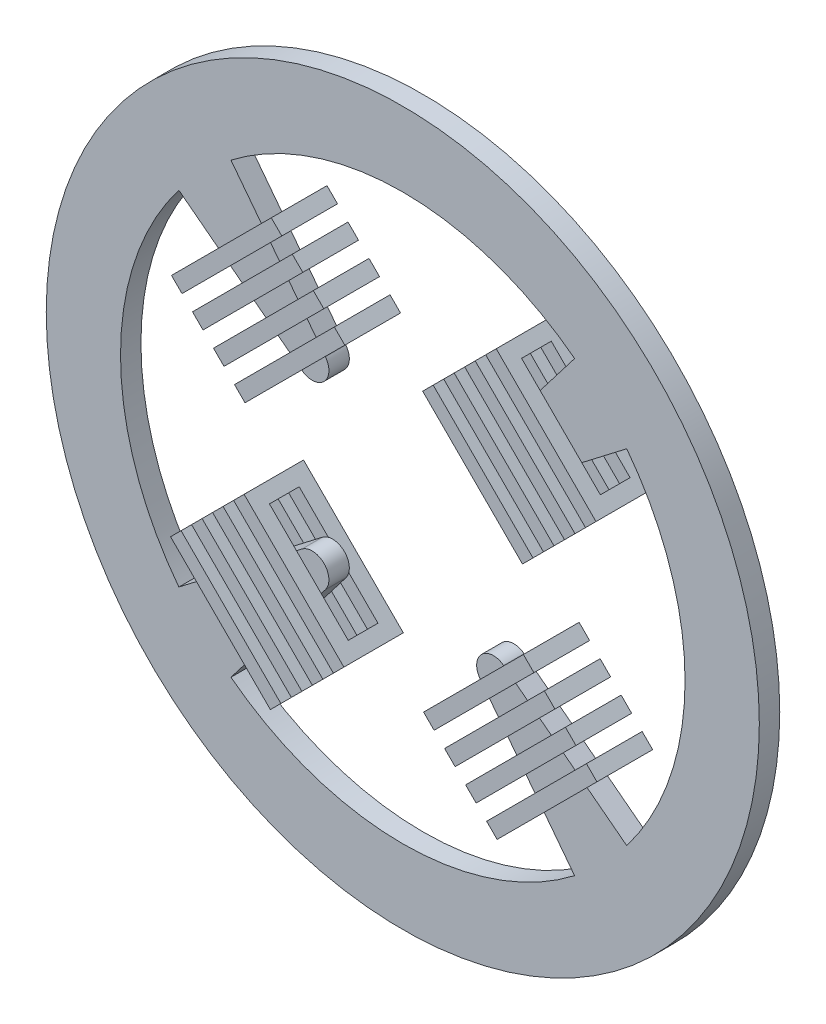
SolidWorks part; units mm, degrees
other "標示1"
sketch "草圖65"
ref_plane "前基準面" through (0, 0, 0) normal (0, 0, 1) x (1, 0, 0)
ref_plane "上基準面" through (0, 0, 0) normal (0, 1, 0) x (1, 0, 0)
ref_plane "右基準面" through (0, 0, 0) normal (1, 0, 0) x (0, 0, -1)
sketch "草圖1" plane through (0, 0, 0) normal (0, 0, 1) x (1, 0, 0)
  circle A0 centre (0, 0) radius 0.96
  circle A1 centre (0, 0) radius 0.76
extrude "填料-伸長1" add sketch "草圖1" along normal blind 0.055
sketch "草圖2" plane through (0, 0, 0.055) normal (0, 0, 1) x (1, 0, 0)
  line L0 (0, 0) -> (0, 1.565) construction
  line L1 (0, 0) -> (-1.8584, 0) construction
  line L2 (-0.0447, 0.3392) -> (-0.0992, 0.7535)
  line L3 (0.0447, 0.3392) -> (0.0992, 0.7535)
  line L4 (0.2714, 0.2082) -> (0.6029, 0.4627)
  line L5 (0.2082, 0.2714) -> (0.4627, 0.6029)
  line L6 (0.2082, -0.2714) -> (0.4627, -0.6029)
  line L7 (0.2714, -0.2082) -> (0.6029, -0.4627)
  line L8 (-0.2714, -0.2082) -> (-0.6029, -0.4627)
  line L9 (-0.2082, -0.2714) -> (-0.4627, -0.6029)
  line L10 (-0.2082, 0.2714) -> (-0.4627, 0.6029)
  line L11 (-0.2714, 0.2082) -> (-0.6029, 0.4627)
  circle A0 centre (0, 0) radius 0.3
  circle A1 centre (0, 0) radius 0.76 construction
  arc A3 (-0.0447, 0.3392) -> (0.0447, 0.3392) centre (0, 0.345) ccw
  arc A4 (0.0992, 0.7535) -> (-0.0992, 0.7535) centre (0, 0) ccw
  arc A5 (-0.76, 0) -> (0.76, 0) centre (0, 0) ccw
  arc A6 (0.6029, 0.4627) -> (0.4627, 0.6029) centre (0, 0) ccw
  arc A7 (0.2082, 0.2714) -> (0.2714, 0.2082) centre (0.244, 0.244) ccw
  arc A8 (0.4627, -0.6029) -> (0.6029, -0.4627) centre (0, 0) ccw
  arc A9 (0.2714, -0.2082) -> (0.2082, -0.2714) centre (0.244, -0.244) ccw
  arc A10 (-0.6029, -0.4627) -> (-0.4627, -0.6029) centre (0, 0) ccw
  arc A11 (-0.2082, -0.2714) -> (-0.2714, -0.2082) centre (-0.244, -0.244) ccw
  arc A12 (-0.4627, 0.6029) -> (-0.6029, 0.4627) centre (0, 0) ccw
  arc A13 (-0.2714, 0.2082) -> (-0.2082, 0.2714) centre (-0.244, 0.244) ccw
  point P23 (0, 0)
  point P34 (0, 0)
  point P41 (0, 0)
  circle M4 centre (0, 0) radius 0.76
  dimension "D1" = 7.5
  dimension "D3" = 2
  dimension "D4" = 4
  dimension "D2" = 7.5
extrude "填料-伸長2" add sketch "草圖2" against normal blind 0.055 contours L11 A13 L10 M4 | L5 A7 L4 M4 | L7 A9 L6 M4 | A11 L8 L9 M4
sketch "草圖7" plane through (0, 0, 0.055) normal (0, 0, 1) x (1, 0, 0)
  line L0 (0.2121, 0.2121) -> (0.2404, 0.2404) construction
  line L1 (0.2404, 0.2404) -> (0.2013, 0.2795) construction
  line L2 (0.2404, 0.2404) -> (0.5894, 0.5894) construction
  line L3 (0.0244, -0.0244) -> (-0.6648, 0.6648) construction
  line L4 (0.2404, -0.2404) -> (0.3328, -0.148)
  arc A0 (0.2082, 0.2714) -> (0.2714, 0.2082) centre (0.244, 0.244) ccw construction
  arc A1 (-0.2082, -0.2714) -> (-0.2714, -0.2082) centre (-0.244, -0.244) ccw construction
  arc A2 (-0.2714, 0.2082) -> (-0.2082, 0.2714) centre (-0.244, 0.244) ccw construction
  arc A3 (0.2714, -0.2082) -> (0.2082, -0.2714) centre (0.244, -0.244) ccw construction
  point P5 (0.297, 0.297)
  point P7 (-0.2121, -0.2121)
  point P8 (0.3536, 0.3536)
  point P9 (0.4101, 0.4101)
  point P12 (-0.2404, -0.2404)
  point P16 (-0.297, -0.297)
  point P17 (-0.3536, -0.3536)
  point P18 (-0.4101, -0.4101)
  point P20 (0.2404, -0.2404)
  point P23 (-0.2404, 0.2404)
  point P24 (-0.2121, 0.2121)
  point P25 (0.2121, -0.2121)
  point P29 (0.297, -0.297)
  point P33 (0.3536, -0.3536)
  point P34 (0.4101, -0.4101)
  point P35 (-0.297, 0.297)
  point P36 (-0.3536, 0.3536)
  point P37 (-0.4101, 0.4101)
  point P40 (0.4667, -0.4667)
  point P41 (0.5233, -0.5233)
  point P42 (0.4667, 0.4667)
  point P43 (0.5233, 0.5233)
  point P44 (-0.4667, 0.4667)
  point P45 (-0.5233, 0.5233)
  point P46 (-0.4667, -0.4667)
  point P47 (-0.5233, -0.5233)
  point P48 (0, 0)
  dimension "D1" = 0.08
  dimension "D2" = 0.08
  dimension "D3" = 0.08
  dimension "D4" = 0.04
  dimension "D5" = 0.04
  dimension "D6" = 0.08
  dimension "D7" = 0.08
  dimension "D8" = 0.08
  dimension "D9" = 0.04
  dimension "D10" = 0.04
  dimension "D11" = 0.08
  dimension "D12" = 0.08
  dimension "D13" = 0.08
  dimension "D14" = 0.08
  dimension "D15" = 0.08
  dimension "D16" = 0.08
  dimension "D17" = 0.08
  dimension "D18" = 0.08
  dimension "D19" = 0.08
  dimension "D20" = 0.08
  dimension "D21" = 0.08
  dimension "D22" = 0.08
  dimension "D23" = 0.08
  dimension "D24" = 0.08
ref_plane "平面5" through (0.2404, 0.2404, 0) normal (0.7071, 0.7071, 0) x (-0.7071, 0.7071, 0)
sketch "草圖11" plane through (0.2404, 0.2404, 0) normal (0.7071, 0.7071, 0) x (-0.7071, 0.7071, 0)
  line L0 (0, 0.055) -> (0, 0.1261) construction
  line L1 (-0.15, 0.0675) -> (0.15, 0.0675)
  line L2 (0.19, 0.1075) -> (-0.19, 0.1075)
  line L7 (-0.19, -0.0525) -> (0.19, -0.0525)
  line L17 (0.19, 0.1075) -> (0.19, -0.0525)
  line L18 (-0.19, 0.1075) -> (-0.19, -0.0525)
  line L19 (-0.15, -0.0125) -> (0.15, -0.0125)
  line L20 (-0.15, 0.0675) -> (-0.15, -0.0125)
  line L21 (0.15, 0.0675) -> (0.15, -0.0125)
  point P1 (0, 0.0275)
  point P2 (0, -0.0125)
  point P9 (0, 0.055)
  point P10 (0, -0.0525)
  point P11 (0, 0)
  point P13 (0, 0.1075)
  point P16 (0, -0.0525)
  point P19 (0, 0.0675)
  point P21 (0, 0.0675)
  point P22 (0, 0.1075)
  point P24 (0, -0.0125)
  dimension "D1" = 0.04
  dimension "D2" = 0.04
  dimension "D3" = 0.38
  dimension "D4" = 0.04
  dimension "D7" = 0.04
extrude "填料-伸長3" add sketch "草圖11" along normal blind 0.04 separate body
ref_plane "平面6" through (0.297, 0.297, 0) normal (0.7071, 0.7071, 0) x (0.7071, -0.7071, 0)
ref_plane "平面7" through (0.3536, 0.3536, 0) normal (0.7071, 0.7071, 0) x (0.7071, -0.7071, 0)
ref_plane "平面8" through (0.4101, 0.4101, 0) normal (0.7071, 0.7071, 0) x (0.7071, -0.7071, 0)
ref_plane "平面9" through (-0.2404, -0.2404, 0) normal (0.7071, 0.7071, 0) x (0.7071, -0.7071, 0)
ref_plane "平面10" through (-0.297, -0.297, 0) normal (0.7071, 0.7071, 0) x (0.7071, -0.7071, 0)
ref_plane "平面11" through (-0.3536, -0.3536, 0) normal (0.7071, 0.7071, 0) x (0.7071, -0.7071, 0)
ref_plane "平面12" through (-0.4101, -0.4101, 0) normal (0.7071, 0.7071, 0) x (0.7071, -0.7071, 0)
ref_plane "平面13" through (0.2404, -0.2404, 0) normal (0.7071, -0.7071, 0) x (0.7071, 0.7071, 0)
ref_plane "平面14" through (0.297, -0.297, 0) normal (0.7071, -0.7071, 0) x (0, 0, -1)
ref_plane "平面15" through (0.3536, -0.3536, 0) normal (0.7071, -0.7071, 0) x (0, 0, -1)
ref_plane "平面16" through (0.4101, -0.4101, 0) normal (0.7071, -0.7071, 0) x (0, 0, -1)
ref_plane "平面17" through (-0.2404, 0.2404, 0) normal (0.7071, -0.7071, 0) x (0, 0, -1)
ref_plane "平面18" through (-0.297, 0.297, 0) normal (0.7071, -0.7071, 0) x (0, 0, -1)
ref_plane "平面19" through (-0.3536, 0.3536, 0) normal (0.7071, -0.7071, 0) x (0, 0, -1)
ref_plane "平面20" through (-0.4101, 0.4101, 0) normal (0.7071, -0.7071, 0) x (0, 0, -1)
sketch "草圖60" plane through (0.2404, -0.2404, 0) normal (0.7071, -0.7071, 0) x (0.7071, 0.7071, 0)
sketch "草圖62" plane through (0.2404, -0.2404, 0) normal (0.7071, -0.7071, 0) x (0.7071, 0.7071, 0)
  line L0 (0, -0.0586) -> (0, 0.1686)
  line L2 (0.15, 0.065) -> (-0.15, 0.065)
  line L3 (-0.15, 0.065) -> (-0.15, -0.005)
  line L4 (-0.15, -0.005) -> (0.15, -0.005)
  line L5 (0.15, -0.005) -> (0.15, 0.065)
  line L6 (0.19, 0.105) -> (-0.19, 0.105)
  line L7 (-0.19, 0.105) -> (-0.19, -0.045)
  line L8 (-0.19, -0.045) -> (0.19, -0.045)
  line L9 (0.19, -0.045) -> (0.19, 0.105)
  point P0 (0, 0.065)
  point P4 (0, 0.055)
  point P5 (0, -0.005)
  point P8 (0, 0.105)
  point P11 (0, 0.065)
  point P14 (0, -0.045)
  point P18 (0, 0.105)
  dimension "D1" = 0.01
  dimension "D2" = 0.06
  dimension "D3" = 0.04
  dimension "D4" = 0.04
  dimension "D5" = 0.38
  dimension "D6" = 0.3
sketch "草圖64" plane through (0.297, -0.297, 0) normal (0.7071, -0.7071, 0) x (0, 0, -1)
  line L0 (0.045, 0.19) -> (-0.105, 0.19) construction
  line L1 (0.005, 0.15) -> (-0.065, 0.15) construction
  line L2 (0.045, -0.19) -> (0.045, 0.19) construction
  line L3 (0.005, -0.15) -> (0.005, 0.15) construction
  line L4 (-0.065, -0.15) -> (0.005, -0.15) construction
  line L5 (-0.065, 0.15) -> (-0.065, -0.15) construction
  line L6 (-0.105, -0.19) -> (0.045, -0.19) construction
  line L7 (-0.105, 0.19) -> (-0.105, -0.19) construction
  line L8 (0.045, 0.19) -> (-0.105, 0.19)
  line L9 (0.005, 0.15) -> (-0.065, 0.15)
  line L10 (0.045, -0.19) -> (0.045, 0.19)
  line L11 (0.005, -0.15) -> (0.005, 0.15)
  line L12 (-0.065, -0.15) -> (0.005, -0.15)
  line L13 (-0.065, 0.15) -> (-0.065, -0.15)
  line L14 (-0.105, -0.19) -> (0.045, -0.19)
  line L15 (-0.105, 0.19) -> (-0.105, -0.19)
sketch "草圖68" plane through (0.3536, -0.3536, 0) normal (0.7071, -0.7071, 0) x (0, 0, -1)
  line L0 (-0.105, -0.19) -> (0.045, -0.19) construction
  line L1 (-0.065, -0.15) -> (0.005, -0.15) construction
  line L2 (0.005, -0.15) -> (0.005, 0.15) construction
  line L3 (-0.065, 0.15) -> (-0.065, -0.15) construction
  line L4 (0.005, 0.15) -> (-0.065, 0.15) construction
  line L5 (0.045, -0.19) -> (0.045, 0.19) construction
  line L6 (0.045, 0.19) -> (-0.105, 0.19) construction
  line L7 (-0.105, 0.19) -> (-0.105, -0.19) construction
  line L8 (-0.105, -0.19) -> (0.045, -0.19)
  line L9 (-0.065, -0.15) -> (0.005, -0.15)
  line L10 (0.005, -0.15) -> (0.005, 0.15)
  line L11 (-0.065, 0.15) -> (-0.065, -0.15)
  line L12 (0.005, 0.15) -> (-0.065, 0.15)
  line L13 (0.045, -0.19) -> (0.045, 0.19)
  line L14 (0.045, 0.19) -> (-0.105, 0.19)
  line L15 (-0.105, 0.19) -> (-0.105, -0.19)
sketch "草圖69" plane through (0.4101, -0.4101, 0) normal (0.7071, -0.7071, 0) x (0, 0, -1)
  line L0 (0.045, -0.19) -> (0.045, 0.19) construction
  line L1 (0.045, 0.19) -> (-0.105, 0.19) construction
  line L2 (-0.105, 0.19) -> (-0.105, -0.19) construction
  line L3 (-0.105, -0.19) -> (0.045, -0.19) construction
  line L4 (-0.065, -0.15) -> (0.005, -0.15) construction
  line L5 (0.005, -0.15) -> (0.005, 0.15) construction
  line L6 (-0.065, 0.15) -> (-0.065, -0.15) construction
  line L7 (0.005, 0.15) -> (-0.065, 0.15) construction
  line L8 (0.045, -0.19) -> (0.045, 0.19)
  line L9 (0.045, 0.19) -> (-0.105, 0.19)
  line L10 (-0.105, 0.19) -> (-0.105, -0.19)
  line L11 (-0.105, -0.19) -> (0.045, -0.19)
  line L12 (-0.065, -0.15) -> (0.005, -0.15)
  line L13 (0.005, -0.15) -> (0.005, 0.15)
  line L14 (-0.065, 0.15) -> (-0.065, -0.15)
  line L15 (0.005, 0.15) -> (-0.065, 0.15)
sketch "草圖70" plane through (-0.2404, 0.2404, 0) normal (0.7071, -0.7071, 0) x (0, 0, -1)
  line L0 (-0.105, 0.19) -> (-0.105, -0.19) construction
  line L1 (-0.105, -0.19) -> (0.045, -0.19) construction
  line L2 (-0.065, -0.15) -> (0.005, -0.15) construction
  line L3 (-0.065, 0.15) -> (-0.065, -0.15) construction
  line L4 (0.005, -0.15) -> (0.005, 0.15) construction
  line L5 (0.005, 0.15) -> (-0.065, 0.15) construction
  line L6 (0.045, -0.19) -> (0.045, 0.19) construction
  line L7 (0.045, 0.19) -> (-0.105, 0.19) construction
  line L8 (-0.105, 0.19) -> (-0.105, -0.19)
  line L9 (-0.105, -0.19) -> (0.045, -0.19)
  line L10 (-0.065, -0.15) -> (0.005, -0.15)
  line L11 (-0.065, 0.15) -> (-0.065, -0.15)
  line L12 (0.005, -0.15) -> (0.005, 0.15)
  line L13 (0.005, 0.15) -> (-0.065, 0.15)
  line L14 (0.045, -0.19) -> (0.045, 0.19)
  line L15 (0.045, 0.19) -> (-0.105, 0.19)
sketch "草圖71" plane through (-0.297, 0.297, 0) normal (0.7071, -0.7071, 0) x (0, 0, -1)
  line L0 (0.045, -0.19) -> (0.045, 0.19) construction
  line L1 (-0.105, -0.19) -> (0.045, -0.19) construction
  line L2 (-0.065, -0.15) -> (0.005, -0.15) construction
  line L3 (0.005, -0.15) -> (0.005, 0.15) construction
  line L4 (-0.065, 0.15) -> (-0.065, -0.15) construction
  line L5 (0.005, 0.15) -> (-0.065, 0.15) construction
  line L6 (-0.105, 0.19) -> (-0.105, -0.19) construction
  line L7 (0.045, 0.19) -> (-0.105, 0.19) construction
  line L8 (0.045, -0.19) -> (0.045, 0.19)
  line L9 (-0.105, -0.19) -> (0.045, -0.19)
  line L10 (-0.065, -0.15) -> (0.005, -0.15)
  line L11 (0.005, -0.15) -> (0.005, 0.15)
  line L12 (-0.065, 0.15) -> (-0.065, -0.15)
  line L13 (0.005, 0.15) -> (-0.065, 0.15)
  line L14 (-0.105, 0.19) -> (-0.105, -0.19)
  line L15 (0.045, 0.19) -> (-0.105, 0.19)
sketch "草圖72" plane through (-0.3536, 0.3536, 0) normal (0.7071, -0.7071, 0) x (0, 0, -1)
  line L0 (-0.105, -0.19) -> (0.045, -0.19) construction
  line L1 (-0.105, 0.19) -> (-0.105, -0.19) construction
  line L2 (-0.065, 0.15) -> (-0.065, -0.15) construction
  line L3 (0.005, -0.15) -> (0.005, 0.15) construction
  line L4 (0.005, 0.15) -> (-0.065, 0.15) construction
  line L5 (0.045, 0.19) -> (-0.105, 0.19) construction
  line L6 (0.045, -0.19) -> (0.045, 0.19) construction
  line L7 (-0.105, -0.19) -> (0.045, -0.19)
  line L8 (-0.105, 0.19) -> (-0.105, -0.19)
  line L9 (-0.065, 0.15) -> (-0.065, -0.15)
  line L10 (0.005, -0.15) -> (0.005, 0.15)
  line L11 (0.005, 0.15) -> (-0.065, 0.15)
  line L12 (0.045, 0.19) -> (-0.105, 0.19)
  line L13 (0.045, -0.19) -> (0.045, 0.19)
  line L14 (-0.065, -0.15) -> (0.005, -0.15)
sketch "草圖73" plane through (-0.4101, 0.4101, 0) normal (0.7071, -0.7071, 0) x (0, 0, -1)
  line L0 (-0.065, -0.15) -> (0.005, -0.15) construction
  line L1 (-0.105, -0.19) -> (0.045, -0.19) construction
  line L2 (-0.105, 0.19) -> (-0.105, -0.19) construction
  line L3 (-0.065, 0.15) -> (-0.065, -0.15) construction
  line L4 (0.005, 0.15) -> (-0.065, 0.15) construction
  line L5 (0.005, -0.15) -> (0.005, 0.15) construction
  line L6 (0.045, -0.19) -> (0.045, 0.19) construction
  line L7 (0.045, 0.19) -> (-0.105, 0.19) construction
  line L8 (-0.065, -0.15) -> (0.005, -0.15)
  line L9 (-0.105, -0.19) -> (0.045, -0.19)
  line L10 (-0.105, 0.19) -> (-0.105, -0.19)
  line L11 (-0.065, 0.15) -> (-0.065, -0.15)
  line L12 (0.005, 0.15) -> (-0.065, 0.15)
  line L13 (0.005, -0.15) -> (0.005, 0.15)
  line L14 (0.045, -0.19) -> (0.045, 0.19)
  line L15 (0.045, 0.19) -> (-0.105, 0.19)
sketch "草圖74" plane through (-0.3536, 0.3536, 0) normal (0.7071, -0.7071, 0) x (0, 0, -1)
  line L0 (-0.065, -0.15) -> (0.005, -0.15) construction
  line L1 (-0.065, -0.15) -> (0.005, -0.15)
extrude "填料-伸長28" add sketch "草圖62" along normal blind 0.04 separate body contours L8 L9 L6 L0 L2 L5 L4 | L7 L8 L0 L4 L3 L2 L6
extrude "填料-伸長29" add sketch "草圖64" along normal blind 0.04 separate body
extrude "填料-伸長30" add sketch "草圖68" along normal blind 0.04 separate body
extrude "填料-伸長31" add sketch "草圖69" along normal blind 0.04 separate body
extrude "填料-伸長32" add sketch "草圖70" against normal blind 0.04 separate body
extrude "填料-伸長33" add sketch "草圖71" against normal blind 0.04 separate body
extrude "填料-伸長34" add sketch "草圖72" against normal blind 0.04 separate body
extrude "填料-伸長35" add sketch "草圖73" against normal blind 0.04 separate body
sketch "草圖76" plane through (0.297, 0.297, 0) normal (0.7071, 0.7071, 0) x (0.7071, -0.7071, 0)
  line L0 (0.19, -0.1075) -> (0.19, 0.0525) construction
  line L1 (0.15, -0.0675) -> (0.15, 0.0125) construction
  line L2 (-0.19, -0.1075) -> (0.19, -0.1075) construction
  line L3 (0.15, -0.0675) -> (-0.15, -0.0675) construction
  line L4 (-0.15, -0.0675) -> (-0.15, 0.0125) construction
  line L5 (-0.19, -0.1075) -> (-0.19, 0.0525) construction
  line L6 (0.19, 0.0525) -> (-0.19, 0.0525) construction
  line L7 (0.15, 0.0125) -> (-0.15, 0.0125) construction
  line L8 (0.19, -0.1075) -> (0.19, 0.0525)
  line L9 (0.15, -0.0675) -> (0.15, 0.0125)
  line L10 (-0.19, -0.1075) -> (0.19, -0.1075)
  line L11 (0.15, -0.0675) -> (-0.15, -0.0675)
  line L12 (-0.15, -0.0675) -> (-0.15, 0.0125)
  line L13 (-0.19, -0.1075) -> (-0.19, 0.0525)
  line L14 (0.19, 0.0525) -> (-0.19, 0.0525)
  line L15 (0.15, 0.0125) -> (-0.15, 0.0125)
sketch "草圖77" plane through (0.3536, 0.3536, 0) normal (0.7071, 0.7071, 0) x (0.7071, -0.7071, 0)
  line L0 (0.19, -0.1075) -> (0.19, 0.0525) construction
  line L1 (0.15, -0.0675) -> (0.15, 0.0125) construction
  line L2 (-0.19, -0.1075) -> (0.19, -0.1075) construction
  line L3 (0.15, -0.0675) -> (-0.15, -0.0675) construction
  line L4 (-0.15, -0.0675) -> (-0.15, 0.0125) construction
  line L5 (-0.19, -0.1075) -> (-0.19, 0.0525) construction
  line L6 (0.19, 0.0525) -> (-0.19, 0.0525) construction
  line L7 (0.15, 0.0125) -> (-0.15, 0.0125) construction
  line L8 (0.19, -0.1075) -> (0.19, 0.0525)
  line L9 (0.15, -0.0675) -> (0.15, 0.0125)
  line L10 (-0.19, -0.1075) -> (0.19, -0.1075)
  line L11 (0.15, -0.0675) -> (-0.15, -0.0675)
  line L12 (-0.15, -0.0675) -> (-0.15, 0.0125)
  line L13 (-0.19, -0.1075) -> (-0.19, 0.0525)
  line L14 (0.19, 0.0525) -> (-0.19, 0.0525)
  line L15 (0.15, 0.0125) -> (-0.15, 0.0125)
sketch "草圖78" plane through (0.4101, 0.4101, 0) normal (0.7071, 0.7071, 0) x (0.7071, -0.7071, 0)
  line L0 (0.19, -0.1075) -> (0.19, 0.0525) construction
  line L1 (-0.19, -0.1075) -> (0.19, -0.1075) construction
  line L2 (0.19, 0.0525) -> (-0.19, 0.0525) construction
  line L3 (-0.19, -0.1075) -> (-0.19, 0.0525) construction
  line L4 (0.15, -0.0675) -> (-0.15, -0.0675) construction
  line L5 (0.15, -0.0675) -> (0.15, 0.0125) construction
  line L6 (0.15, 0.0125) -> (-0.15, 0.0125) construction
  line L7 (-0.15, -0.0675) -> (-0.15, 0.0125) construction
  line L8 (0.19, -0.1075) -> (0.19, 0.0525)
  line L9 (-0.19, -0.1075) -> (0.19, -0.1075)
  line L10 (0.19, 0.0525) -> (-0.19, 0.0525)
  line L11 (-0.19, -0.1075) -> (-0.19, 0.0525)
  line L12 (0.15, -0.0675) -> (-0.15, -0.0675)
  line L13 (0.15, -0.0675) -> (0.15, 0.0125)
  line L14 (0.15, 0.0125) -> (-0.15, 0.0125)
  line L15 (-0.15, -0.0675) -> (-0.15, 0.0125)
sketch "草圖79" plane through (-0.2404, -0.2404, 0) normal (0.7071, 0.7071, 0) x (0.7071, -0.7071, 0)
  line L0 (-0.19, -0.1075) -> (0.19, -0.1075) construction
  line L1 (0.15, -0.0675) -> (-0.15, -0.0675) construction
  line L2 (-0.15, -0.0675) -> (-0.15, 0.0125) construction
  line L3 (-0.19, -0.1075) -> (-0.19, 0.0525) construction
  line L4 (0.19, -0.1075) -> (0.19, 0.0525) construction
  line L5 (0.15, -0.0675) -> (0.15, 0.0125) construction
  line L6 (0.15, 0.0125) -> (-0.15, 0.0125) construction
  line L7 (0.19, 0.0525) -> (-0.19, 0.0525) construction
  line L8 (-0.19, -0.1075) -> (0.19, -0.1075)
  line L9 (0.15, -0.0675) -> (-0.15, -0.0675)
  line L10 (-0.15, -0.0675) -> (-0.15, 0.0125)
  line L11 (-0.19, -0.1075) -> (-0.19, 0.0525)
  line L12 (0.19, -0.1075) -> (0.19, 0.0525)
  line L13 (0.15, -0.0675) -> (0.15, 0.0125)
  line L14 (0.15, 0.0125) -> (-0.15, 0.0125)
  line L15 (0.19, 0.0525) -> (-0.19, 0.0525)
sketch "草圖80" plane through (-0.297, -0.297, 0) normal (0.7071, 0.7071, 0) x (0.7071, -0.7071, 0)
  line L0 (-0.19, -0.1075) -> (0.19, -0.1075) construction
  line L1 (0.19, -0.1075) -> (0.19, 0.0525) construction
  line L2 (0.19, 0.0525) -> (-0.19, 0.0525) construction
  line L3 (-0.19, -0.1075) -> (-0.19, 0.0525) construction
  line L4 (-0.15, -0.0675) -> (-0.15, 0.0125) construction
  line L5 (0.15, -0.0675) -> (-0.15, -0.0675) construction
  line L6 (0.15, -0.0675) -> (0.15, 0.0125) construction
  line L7 (0.15, 0.0125) -> (-0.15, 0.0125) construction
  line L8 (-0.19, -0.1075) -> (0.19, -0.1075)
  line L9 (0.19, -0.1075) -> (0.19, 0.0525)
  line L10 (0.19, 0.0525) -> (-0.19, 0.0525)
  line L11 (-0.19, -0.1075) -> (-0.19, 0.0525)
  line L12 (-0.15, -0.0675) -> (-0.15, 0.0125)
  line L13 (0.15, -0.0675) -> (-0.15, -0.0675)
  line L14 (0.15, -0.0675) -> (0.15, 0.0125)
  line L15 (0.15, 0.0125) -> (-0.15, 0.0125)
sketch "草圖81" plane through (-0.3536, -0.3536, 0) normal (0.7071, 0.7071, 0) x (0.7071, -0.7071, 0)
  line L0 (-0.19, -0.1075) -> (0.19, -0.1075) construction
  line L1 (0.19, -0.1075) -> (0.19, 0.0525) construction
  line L2 (0.19, 0.0525) -> (-0.19, 0.0525) construction
  line L3 (-0.19, -0.1075) -> (-0.19, 0.0525) construction
  line L4 (-0.15, -0.0675) -> (-0.15, 0.0125) construction
  line L5 (0.15, -0.0675) -> (-0.15, -0.0675) construction
  line L6 (0.15, -0.0675) -> (0.15, 0.0125) construction
  line L7 (0.15, 0.0125) -> (-0.15, 0.0125) construction
  line L8 (-0.19, -0.1075) -> (0.19, -0.1075)
  line L9 (0.19, -0.1075) -> (0.19, 0.0525)
  line L10 (0.19, 0.0525) -> (-0.19, 0.0525)
  line L11 (-0.19, -0.1075) -> (-0.19, 0.0525)
  line L12 (-0.15, -0.0675) -> (-0.15, 0.0125)
  line L13 (0.15, -0.0675) -> (-0.15, -0.0675)
  line L14 (0.15, -0.0675) -> (0.15, 0.0125)
  line L15 (0.15, 0.0125) -> (-0.15, 0.0125)
sketch "草圖82" plane through (-0.4101, -0.4101, 0) normal (0.7071, 0.7071, 0) x (0.7071, -0.7071, 0)
  line L0 (0.19, -0.1075) -> (0.19, 0.0525) construction
  line L1 (-0.19, -0.1075) -> (0.19, -0.1075) construction
  line L2 (-0.15, -0.0675) -> (-0.15, 0.0125) construction
  line L3 (0.15, -0.0675) -> (-0.15, -0.0675) construction
  line L4 (0.15, -0.0675) -> (0.15, 0.0125) construction
  line L5 (0.15, 0.0125) -> (-0.15, 0.0125) construction
  line L6 (0.19, 0.0525) -> (-0.19, 0.0525) construction
  line L7 (-0.19, -0.1075) -> (-0.19, 0.0525) construction
  line L8 (0.19, -0.1075) -> (0.19, 0.0525)
  line L9 (-0.19, -0.1075) -> (0.19, -0.1075)
  line L10 (-0.15, -0.0675) -> (-0.15, 0.0125)
  line L11 (0.15, -0.0675) -> (-0.15, -0.0675)
  line L12 (0.15, -0.0675) -> (0.15, 0.0125)
  line L13 (0.15, 0.0125) -> (-0.15, 0.0125)
  line L14 (0.19, 0.0525) -> (-0.19, 0.0525)
  line L15 (-0.19, -0.1075) -> (-0.19, 0.0525)
extrude "填料-伸長36" add sketch "草圖76" along normal blind 0.04 separate body
extrude "填料-伸長37" add sketch "草圖77" along normal blind 0.04 separate body
extrude "填料-伸長38" add sketch "草圖78" along normal blind 0.04 separate body
extrude "填料-伸長39" add sketch "草圖79" against normal blind 0.04 separate body
extrude "填料-伸長40" add sketch "草圖80" against normal blind 0.04 separate body
extrude "填料-伸長41" add sketch "草圖81" against normal blind 0.04 separate body
extrude "填料-伸長42" add sketch "草圖82" against normal blind 0.04 separate body
sketch "草圖86" plane through (0.4384, 0.4384, 0) normal (0.7071, 0.7071, 0) x (0, 0, -1)
  line L0 (0.0125, 0.018) -> (0.0525, 0.018)
  line L1 (0.0125, -0.15) -> (0.0125, 0.15) construction
  line L2 (0.0525, -0.19) -> (0.0525, 0.19) construction
  line L3 (0.0525, 0.018) -> (0.0525, 0)
  line L4 (0.0525, 0) -> (0.0125, 0)
  line L5 (0.0125, 0) -> (0.0125, 0.018)
extrude "除料-伸長4" cut sketch "草圖86" against normal blind 0.5
